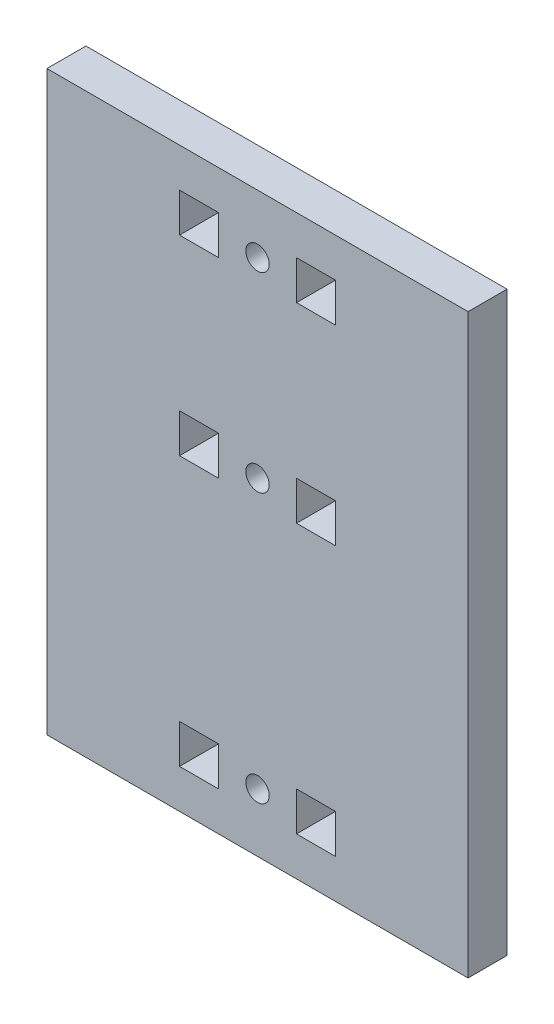
SolidWorks part; units mm, degrees
ref_plane "Front Plane" through (0, 0, 0) normal (0, 0, 1) x (1, 0, 0)
ref_plane "Top Plane" through (0, 0, 0) normal (0, 1, 0) x (1, 0, 0)
ref_plane "Right Plane" through (0, 0, 0) normal (1, 0, 0) x (0, 0, -1)
sketch "Sketch1" plane through (0, 0, 0) normal (0, 0, 1) x (1, 0, 0)
  line L0 (0, 0) -> (-6.7036, 0) construction
  line L1 (-27, -42) -> (27, -42)
  line L2 (-27, -42) -> (-27, 32)
  line L3 (-27, 32) -> (27, 32)
  line L4 (27, -42) -> (27, 32)
  line L7 (0, 0) -> (0, 72.9696) construction
  point P0 (0, 0)
  point P8 (0, 0)
  point P10 (0, 0)
  point P11 (0, 0)
  line B0 (-5, 2.5) -> (-10, 2.5)
  line B1 (-5, 2.5) -> (-5, -2.5)
  line B2 (-5, -2.5) -> (-10, -2.5)
  line B3 (-10, 2.5) -> (-10, -2.5)
  line B4 (5, 2.5) -> (10, 2.5)
  line B5 (5, 2.5) -> (5, -2.5)
  line B6 (5, -2.5) -> (10, -2.5)
  line B7 (10, 2.5) -> (10, -2.5)
  line B8 (0, 0) -> (0, 6.9724) construction
  circle B9 centre (0, 0) radius 1.5
  line B10 (-5, 27) -> (-10, 27)
  line B11 (-5, 27) -> (-5, 22)
  line B12 (-5, 22) -> (-10, 22)
  line B13 (-10, 27) -> (-10, 22)
  line B14 (5, 27) -> (10, 27)
  line B15 (5, 27) -> (5, 22)
  line B16 (5, 22) -> (10, 22)
  line B17 (10, 27) -> (10, 22)
  line B18 (0, 24.5) -> (0, 31.4724) construction
  circle B19 centre (0, 24.5) radius 1.5
  line B20 (-5, -32) -> (-10, -32)
  line B21 (-5, -32) -> (-5, -37)
  line B22 (-5, -37) -> (-10, -37)
  line B23 (-10, -32) -> (-10, -37)
  line B24 (5, -32) -> (10, -32)
  line B25 (5, -32) -> (5, -37)
  line B26 (5, -37) -> (10, -37)
  line B27 (10, -32) -> (10, -37)
  line B28 (0, -34.5) -> (0, -27.5276) construction
  circle B29 centre (0, -34.5) radius 1.5
  dimension "D1" = 34.5
  dimension "D2" = 24.5
  dimension "D3" = 7.5
  dimension "D4" = 7.5
  dimension "D5" = 27
  dimension "D6" = 27
sketch_block_instance "Trou M3 plots 5mm-1"
sketch_block "Trou M3 plots 5mm" parameters "D2"=3, "D1"=5, "D3"=5, "D4"=10
sketch_block_instance "Trou M3 plots 5mm-2"
sketch_block_instance "Trou M3 plots 5mm-3"
extrude "Boss-Extrude1" add sketch "Sketch1" along normal blind 5
